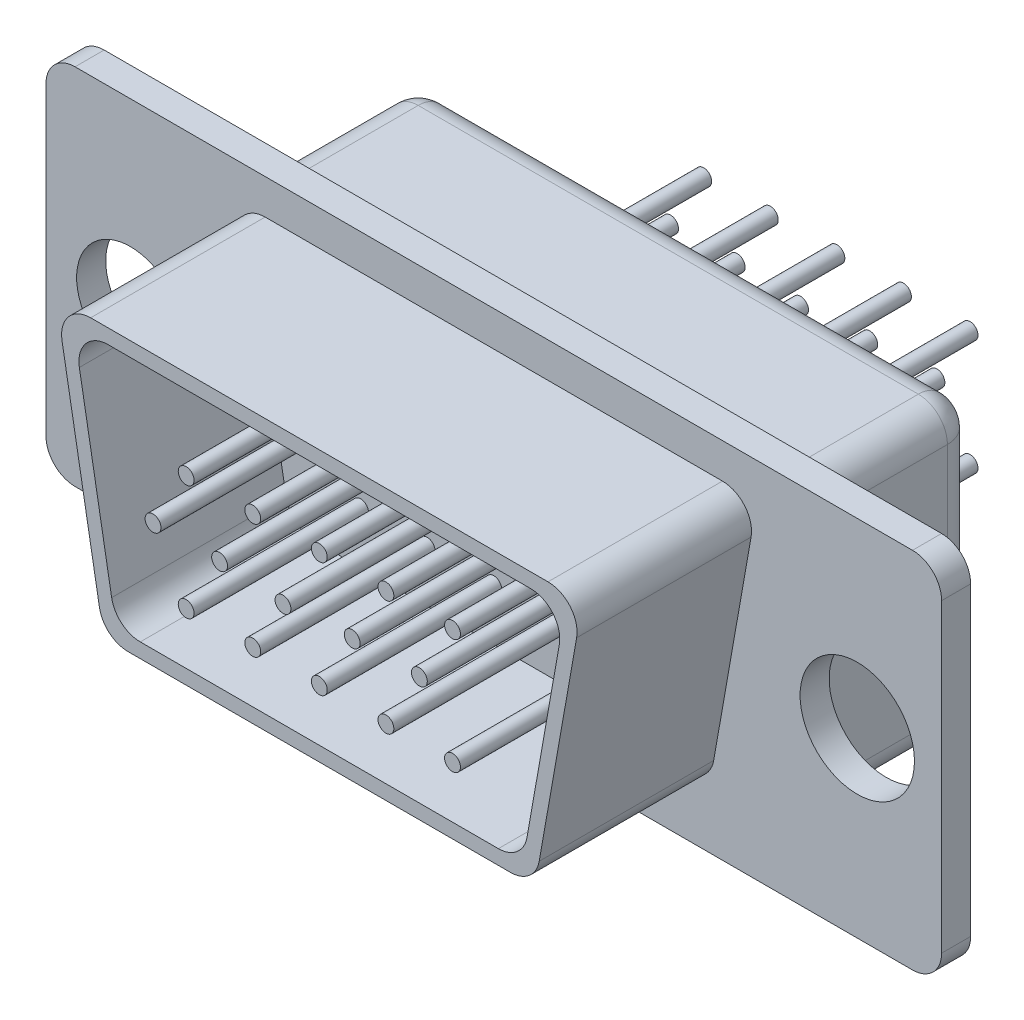
SolidWorks part; units mm, degrees
ref_plane "Plan de face" through (0, 0, 0) normal (0, 0, 1) x (1, 0, 0)
ref_plane "Plan de dessus" through (0, 0, 0) normal (0, 1, 0) x (1, 0, 0)
ref_plane "Plan de droite" through (0, 0, 0) normal (1, 0, 0) x (0, 0, -1)
sketch "Esquisse1" plane through (0, 0, 0) normal (0, 0, 1) x (1, 0, 0)
  line L0 (0, 0) -> (30.8, 12.5) construction
  line L1 (0, 0) -> (30.8, 0)
  line L2 (0, 0) -> (0, 12.5)
  line L3 (0, 12.5) -> (30.8, 12.5)
  line L4 (30.8, 0) -> (30.8, 12.5)
  line L5 (27.9, 6.25) -> (2.9, 6.25) construction
  line L6 (0, 12.5) -> (30.8, 0) construction
  circle A0 centre (2.9, 6.25) radius 1.8473
  circle A1 centre (27.9, 6.25) radius 1.9669
  point P9 (15.4, 6.25)
  dimension "D1" = 30.8
  dimension "D2" = 12.5
  dimension "D3" = 25
extrude "Extrusion1" add sketch "Esquisse1" along normal blind 1
sketch "Esquisse2" plane through (0, 0, 1) normal (0, 0, 1) x (1, 0, 0)
  line L0 (8.1318, 10.7929) -> (22.6682, 10.7929)
  line L1 (23.6531, 9.6193) -> (22.5422, 3.3193)
  line L2 (21.5574, 2.4929) -> (9.2426, 2.4929)
  line L3 (8.2578, 3.3193) -> (7.1469, 9.6193)
  line L4 (0, 0) -> (30.8, 12.5) construction
  line L5 (30.8, 1) -> (30.8, 11.5) construction
  line L6 (0, 12.5) -> (30.8, 0) construction
  line L7 (6.94, 10.7929) -> (22.3965, 2.4929) construction
  line L8 (23.86, 10.7929) -> (8.4035, 2.4929) construction
  line L9 (7.5359, 11.2929) -> (23.2641, 11.2929)
  line L10 (24.2489, 10.1193) -> (22.9617, 2.8193)
  line L11 (21.9769, 1.9929) -> (8.8231, 1.9929)
  line L12 (7.8383, 2.8193) -> (6.5511, 10.1193)
  arc A0 (7.1469, 9.6193) -> (8.1318, 10.7929) centre (8.1318, 9.7929) cw
  arc A1 (6.5511, 10.1193) -> (7.5359, 11.2929) centre (7.5359, 10.2929) cw
  arc A2 (24.2489, 10.1193) -> (23.2641, 11.2929) centre (23.2641, 10.2929) ccw
  arc A3 (23.6531, 9.6193) -> (22.6682, 10.7929) centre (22.6682, 9.7929) ccw
  arc A4 (22.5422, 3.3193) -> (21.5574, 2.4929) centre (21.5574, 3.4929) cw
  arc A5 (21.9769, 1.9929) -> (22.9617, 2.8193) centre (21.9769, 2.9929) ccw
  arc A6 (9.2426, 2.4929) -> (8.2578, 3.3193) centre (9.2426, 3.4929) cw
  arc A7 (7.8383, 2.8193) -> (8.8231, 1.9929) centre (8.8231, 2.9929) ccw
  point P13 (15.4, 6.25)
  point P14 (15.4, 6.25)
  dimension "D9" = 1
  dimension "D1" = 16.92
  dimension "D2" = 100
  dimension "D3" = 100
  dimension "D4" = 8.3
  dimension "D5" = 0.5
  dimension "D6" = 0.5
  dimension "D7" = 0.5
  dimension "D8" = 0.5
extrude "Extrusion2" add sketch "Esquisse2" along normal blind 6
sketch "Esquisse3" plane through (0, 0, 0) normal (0, 0, -1) x (-1, 0, 0)
  line L0 (-25, 1.25) -> (-5.8, 11.25) construction
  line L1 (-25, 11.25) -> (-5.8, 11.25)
  line L2 (-25, 11.25) -> (-25, 1.25)
  line L3 (-25, 1.25) -> (-5.8, 1.25)
  line L4 (-5.8, 11.25) -> (-5.8, 1.25)
  line L5 (-5.8, 1.25) -> (-25, 11.25) construction
  line L6 (-30.8, 12.5) -> (0, 0) construction
  line L8 (0, 12.5) -> (-30.8, 0) construction
  point P8 (-15.4, 6.25)
  point P13 (-15.4, 6.25)
  dimension "D1" = 19.2
  dimension "D2" = 10
extrude "Extrusion3" add sketch "Esquisse3" along normal blind 6
sketch "Esquisse4" plane through (0, 0, -6) normal (0, 0, -1) x (-1, 0, 0)
  line L0 (-19.98, 8.23) -> (-10.82, 8.23) construction
  line L1 (-10.82, 8.23) -> (-9.544, 6.0138) construction
  line L2 (-10.82, 4.27) -> (-19.98, 4.27) construction
  line L3 (-19.98, 8.23) -> (-19.98, 4.27) construction
  line L4 (-17.69, 8.23) -> (-16.3999, 5.9892) construction
  line L5 (-15.4, 8.23) -> (-14.0179, 5.8295) construction
  line L6 (-13.11, 8.23) -> (-11.834, 6.0138) construction
  line L7 (-18.84, 6.25) -> (-9.68, 6.25) construction
  line L8 (-18.84, 6.25) -> (-19.98, 8.23) construction
  line L9 (-17.69, 4.27) -> (-17.69, 8.23) construction
  line L10 (-15.4, 8.23) -> (-15.4, 4.27) construction
  line L11 (-13.11, 8.23) -> (-13.11, 4.27) construction
  line L12 (-10.82, 4.27) -> (-10.82, 8.23) construction
  line L13 (-25, 1.25) -> (-5.8, 11.25) construction
  line L14 (-25, 11.25) -> (-5.8, 1.25) construction
  circle A0 centre (-19.98, 8.23) radius 0.2725
  circle A1 centre (-17.69, 8.23) radius 0.2725
  circle A2 centre (-15.4, 8.23) radius 0.2725
  circle A3 centre (-13.11, 8.23) radius 0.2725
  circle A4 centre (-10.82, 8.23) radius 0.2725
  circle A5 centre (-9.68, 6.25) radius 0.2725
  circle A6 centre (-11.97, 6.25) radius 0.2725
  circle A7 centre (-14.1497, 6.0681) radius 0.2725
  circle A8 centre (-16.5297, 6.2288) radius 0.2725
  circle A9 centre (-18.84, 6.25) radius 0.2725
  circle A10 centre (-19.98, 4.27) radius 0.2725
  circle A11 centre (-17.69, 4.27) radius 0.2725
  circle A12 centre (-15.4, 4.27) radius 0.2725
  circle A13 centre (-13.11, 4.27) radius 0.2725
  circle A14 centre (-10.82, 4.27) radius 0.2725
  point P13 (-16.55, 6.25)
  point P14 (-14.26, 6.25)
  point P15 (-11.97, 6.25)
  point P39 (-15.4, 6.25)
  dimension "D1" = 2.29
  dimension "D2" = 2.29
  dimension "D3" = 2.29
  dimension "D4" = 2.29
  dimension "D5" = 1.98
  dimension "D6" = 1.98
  dimension "D7" = 1.14
extrude "Extrusion4" add sketch "Esquisse4" along normal blind 4.8
fillet "Congé1" radius 1 12 edges at (15.4, 1.25, -6) (5.8, 6.25, -6) (5.8, 1.25, -3) (5.8, 11.25, -3) (15.4, 11.25, -6) (25, 11.25, -3) (25, 6.25, -6) (25, 1.25, -3) (30.8, 0, 0.5) (30.8, 12.5, 0.5) (0, 0, 0.5) (0, 12.5, 0.5)
sketch "Esquisse7" plane through (0, 0, 1) normal (0, 0, 1) x (1, 0, 0)
  circle A0 centre (19.98, 8.23) radius 0.2725
  circle A1 centre (17.69, 8.23) radius 0.2725
  circle A2 centre (15.4, 8.23) radius 0.2725
  circle A3 centre (13.11, 8.23) radius 0.2725
  circle A4 centre (10.82, 8.23) radius 0.2725
  circle A5 centre (9.68, 6.25) radius 0.2725
  circle A6 centre (11.97, 6.25) radius 0.2725
  circle A7 centre (14.1497, 6.0681) radius 0.2725
  circle A8 centre (16.5297, 6.2288) radius 0.2725
  circle A9 centre (18.84, 6.25) radius 0.2725
  circle A10 centre (19.98, 4.27) radius 0.2725
  circle A11 centre (17.69, 4.27) radius 0.2725
  circle A12 centre (15.4, 4.27) radius 0.2725
  circle A13 centre (13.11, 4.27) radius 0.2725
  circle A14 centre (10.82, 4.27) radius 0.2725
extrude "Extrusion6" add sketch "Esquisse7" along normal up to surface (6 mm away) up to face at (15.4, 6.5687, 7)
